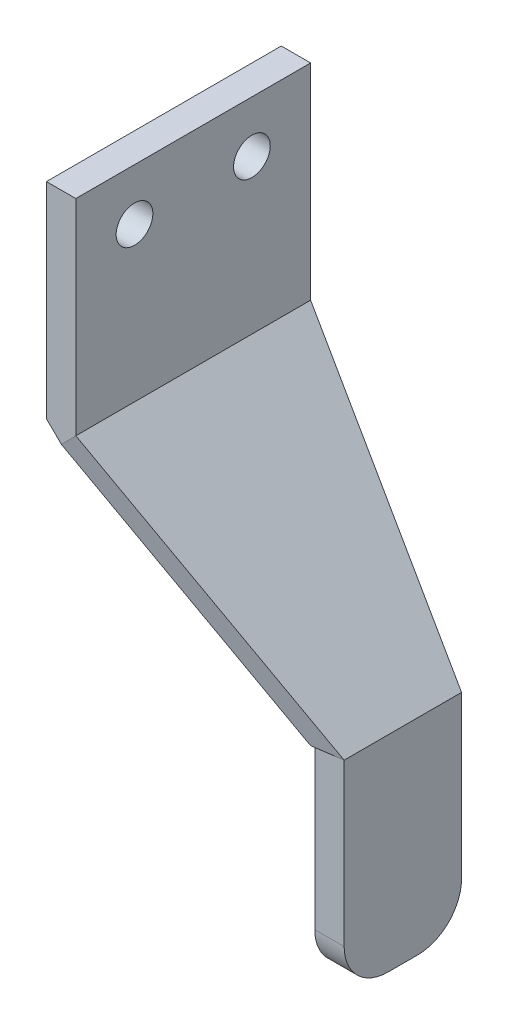
SolidWorks part; units mm, degrees
ref_plane "Plan de face" through (0, 0, 0) normal (0, 0, 1) x (1, 0, 0)
ref_plane "Plan de dessus" through (0, 0, 0) normal (0, 1, 0) x (1, 0, 0)
ref_plane "Plan de droite" through (0, 0, 0) normal (1, 0, 0) x (0, 0, -1)
sketch "Esquisse1" plane through (0, 0, 0) normal (0, 0, 1) x (1, 0, 0)
  line L0 (-4.285, 10.5) -> (-4.285, 3.5)
  line L1 (-4.285, 10.5) -> (-3.285, 10.5)
  line L2 (-3.285, 10.5) -> (-3.285, 3.5)
  line L3 (-3.285, 3.5) -> (3.8564, -3.5)
  line L4 (-4.285, 3.5) -> (2.8564, -3.5)
  line L5 (2.8564, -3.5) -> (2.8564, -10.5)
  line L6 (2.8564, -10.5) -> (3.8564, -10.5)
  line L7 (3.8564, -10.5) -> (3.8564, -3.5)
  dimension "D1" = 7
  dimension "D2" = 1
  dimension "D3" = 7
  dimension "D4" = 10
  dimension "D5" = 7
  dimension "D6" = 1
  dimension "D7" = 7
  dimension "D8" = 0.5
  dimension "D9" = 10.5
extrude "Boss.-Extru.1" add sketch "Esquisse1" along normal blind 8 contours L7 L3 L2 L1 L0 L4 L5 L6
sketch "Esquisse2" plane through (-3.285, 0, 0) normal (1, 0, 0) x (0, 0, -1)
  line L0 (-8, 10.5) -> (-8, 3.5) construction
  circle A0 centre (-6, 8.7446) radius 0.625
  circle A1 centre (-2, 8.7446) radius 0.625
  point P0 (-6, 8.7446)
  point P1 (-2.0294, 8.7446)
  dimension "D2" = 1.25
  dimension "D1" = 2
  dimension "D3" = 2
extrude "Enlèv. mat.-Extru.2" cut sketch "Esquisse2" against normal blind 8
sketch "Esquisse3" plane through (0.14, 0.1428, 0) normal (0.7, 0.7141, 0) x (0.7141, -0.7, 0)
  line L0 (5.204, -8) -> (5.204, 0) construction
  line L1 (-4.796, -8) -> (5.204, -6)
  line L2 (-4.796, 0) -> (5.204, -2)
  line L4 (-4.796, 0) -> (5.204, 0)
  line L5 (5.204, 0) -> (5.204, -2)
  line L6 (5.204, -6) -> (5.204, -8)
  line L7 (5.204, -8) -> (-4.796, -8)
  point P0 (5.204, -6)
  point P1 (5.204, -2)
  dimension "D1" = 2
  dimension "D3" = 2
  dimension "D2" = 2
extrude "Enlèv. mat.-Extru.4" cut sketch "Esquisse3" against normal blind 8
sketch "Esquisse4" plane through (3.8564, 0, 0) normal (1, 0, 0) x (0, 0, -1)
  line L0 (-6, -3.5) -> (-6, -10.5)
  line L1 (-8, -10.5) -> (0, -10.5) construction
  line L2 (-2, -3.5) -> (-2, -10.5)
  line L3 (-6, -10.5) -> (-8, -10.5)
  line L4 (-8, -10.5) -> (-8, -3.5)
  line L5 (-8, -3.5) -> (-6, -3.5)
  line L6 (-2, -3.5) -> (0, -3.5)
  line L7 (0, -3.5) -> (0, -10.5)
  line L8 (0, -10.5) -> (-2, -10.5)
extrude "Enlèv. mat.-Extru.6" cut sketch "Esquisse4" against normal blind 8
fillet "Congé4" radius 1.5 1 edges at (3.3564, -10.5, 2)
fillet "Congé7" radius 1.5 1 edges at (3.3564, -10.5, 6)
